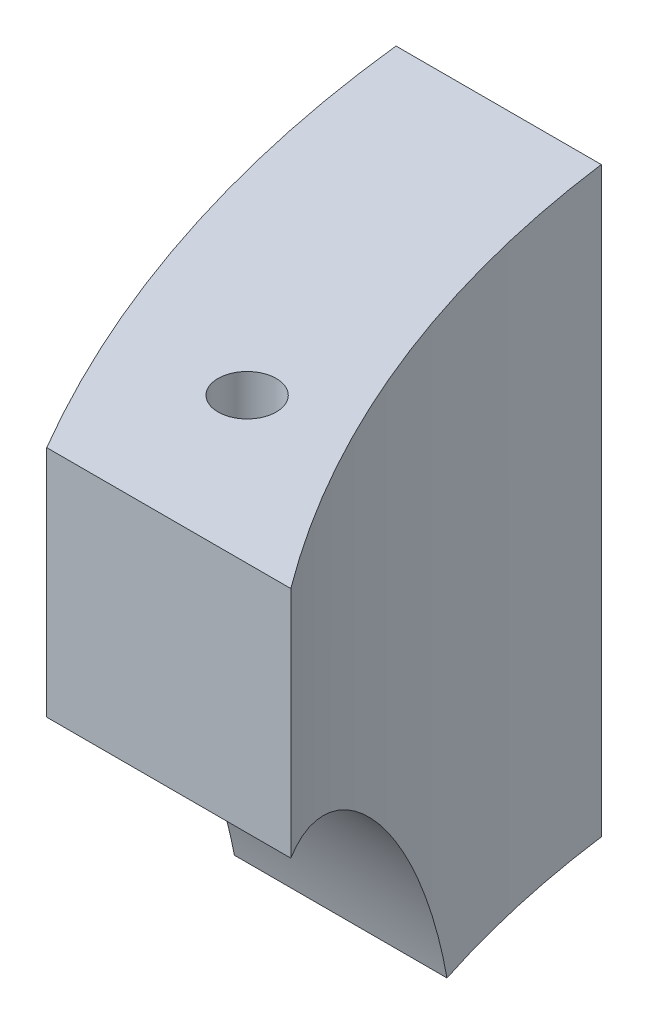
SolidWorks part; units mm, degrees
material "1023 Carbon Steel Sheet (SS)"
ref_plane "Front Plane" through (0, 0, 0) normal (0, 0, 1) x (1, 0, 0)
ref_plane "Top Plane" through (0, 0, 0) normal (0, 1, 0) x (1, 0, 0)
ref_plane "Right Plane" through (0, 0, 0) normal (1, 0, 0) x (0, 0, -1)
sketch "Sketch1" plane through (0, 0, 0) normal (0, 1, 0) x (1, 0, 0)
  line L0 (-1000, 0) -> (-104.805, 0) construction
  line L1 (0, -1000) -> (0, 49000) construction
  line L2 (91.805, -10) -> (90.2527, -10)
  line L3 (-76.805, 0) -> (76.805, 0)
  line L7 (-91.805, -10) -> (-90.2527, -10)
  line L9 (104.805, 0) -> (49000, 0) construction
  line L10 (-76.805, 0) -> (-76.805, 20)
  line L12 (-76.805, 0) -> (76.805, 0) construction
  line L13 (91.805, 20) -> (91.805, -10)
  line L14 (76.805, 20) -> (91.805, 20)
  line L17 (-76.805, 20) -> (-91.805, 20)
  line L18 (76.805, 0) -> (76.805, 20)
  line L19 (-91.805, 20) -> (-91.805, -10)
  arc A0 (-90.2527, -10) -> (90.2527, -10) centre (0, 0) ccw
  arc A1 (-76.805, 0) -> (76.805, 0) centre (0, 0) ccw
  dimension "D1" = 181.61
  dimension "D2" = 14
  dimension "D3" = 30
  dimension "D4" = 15
extrude "Boss-Extrude1" add sketch "Sketch1" against normal blind 60
sketch "Sketch25" plane through (0, -60, 0) normal (0, -1, 0) x (-1, 0, 0)
  line L0 (76.805, 20) -> (91.805, -10)
  line L1 (91.805, -10) -> (76.805, -10)
  line L2 (76.805, -10) -> (91.805, 20)
  line L3 (-91.805, -10) -> (-76.805, 20)
  line L4 (81.555, -3.5) -> (87.055, -3.5)
  line L5 (81.555, -3.5) -> (81.555, 13.5)
  line L6 (81.555, 13.5) -> (87.055, 13.5)
  line L7 (87.055, -3.5) -> (87.055, 13.5)
  line L8 (81.555, -3.5) -> (87.055, 13.5) construction
  line L9 (81.555, 13.5) -> (87.055, -3.5) construction
  line L10 (-76.805, 20) -> (-77.8097, -10)
  line L11 (-77.8097, -10) -> (-91.805, -10)
  line L12 (-77.8097, -10) -> (-91.805, 20)
  line L14 (-87.055, -3.5) -> (-81.555, -3.5)
  line L15 (-87.055, -3.5) -> (-87.055, 13.5)
  line L16 (-87.055, 13.5) -> (-81.555, 13.5)
  line L17 (-81.555, -3.5) -> (-81.555, 13.5)
  line L18 (-87.055, -3.5) -> (-81.555, 13.5) construction
  line L19 (-87.055, 13.5) -> (-81.555, -3.5) construction
  point P4 (84.305, 5)
  point P16 (-84.305, 5)
  dimension "D1" = 5.5
  dimension "D2" = 17
  dimension "D3" = 17
  dimension "D4" = 5.5
extrude "Boss-Extrude3" add sketch "Sketch25" along normal blind 20 contours L15 L16 L17 L14 | L5 L6 L7 L4
ref_plane "Plane4" through (0, 0, 90) normal (0, 0, 1) x (1, 0, 0)
fillet "Fillet1" radius 2.3 8 edges at (84.305, -60, 3.5) (81.555, -60, -5) (84.305, -60, -13.5) (87.055, -60, -5) (-87.055, -60, -5) (-84.305, -60, -13.5) (-84.305, -60, 3.5) (-81.555, -60, -5)
sketch "Sketch28" plane through (91.805, 0, 0) normal (1, 0, 0) x (0, 0, -1)
  line L2 (20, 0) -> (20, -60)
  line L3 (20, -60) -> (-10, -60)
  line L4 (-10, 0) -> (-10, -60)
  line L5 (9, -37) -> (1, -37)
  line L6 (9, -37) -> (9, -47)
  line L7 (9, -47) -> (1, -47)
  line L8 (1, -37) -> (1, -47)
  line L9 (9, -37) -> (1, -47) construction
  line L10 (9, -47) -> (1, -37) construction
  point P7 (5, -42)
  dimension "D1" = 11
  dimension "D2" = 8
  dimension "D3" = 10
  dimension "D4" = 13
extrude "Cut-Extrude17" cut sketch "Sketch28" against normal blind 265 contours L5 L8 L7 L6
sketch "Sketch30" plane through (0, 0, -20) normal (0, 0, -1) x (-1, 0, 0)
  line L0 (-91.805, -60) -> (-91.805, 0) construction
  line L1 (91.805, 0) -> (-91.805, 0)
  line L2 (91.805, 0) -> (91.805, -30)
  line L3 (91.805, -30) -> (-91.805, -30)
  line L4 (-91.805, 0) -> (-91.805, -30)
  dimension "D1" = 30
extrude "Cut-Extrude19" cut sketch "Sketch30" against normal through all both and the other way through all
sketch "Sketch32" plane through (0, 0, -20) normal (0, 0, -1) x (-1, 0, 0)
  line L0 (-91.805, -60) -> (-91.805, -30) construction
  line L1 (-82.805, -39) -> (-85.805, -39)
  line L2 (-82.805, -39) -> (-82.805, -53)
  line L3 (-82.805, -53) -> (-85.805, -53)
  line L4 (-85.805, -39) -> (-85.805, -53)
  line L8 (-76.805, -30) -> (-91.805, -30) construction
  line L9 (0, 0) -> (0, -102.7115)
  line L10 (53.2739, -37) -> (53.2739, -51)
  line L11 (-66.6352, -37) -> (-63.6352, -37)
  line L12 (-66.6352, -37) -> (-66.6352, -51)
  line L13 (-66.6352, -51) -> (-63.6352, -51)
  line L14 (-63.6352, -37) -> (-63.6352, -51)
  line L15 (-50.2739, -37) -> (-53.2739, -37)
  line L16 (-50.2739, -37) -> (-50.2739, -51)
  line L17 (-50.2739, -51) -> (-53.2739, -51)
  line L18 (-53.2739, -37) -> (-53.2739, -51)
  line L19 (50.2739, -51) -> (53.2739, -51)
  line L20 (50.2739, -37) -> (50.2739, -51)
  line L21 (50.2739, -37) -> (53.2739, -37)
  line L22 (63.6352, -37) -> (63.6352, -51)
  line L23 (66.6352, -51) -> (63.6352, -51)
  line L24 (66.6352, -37) -> (66.6352, -51)
  line L25 (66.6352, -37) -> (63.6352, -37)
  line L26 (85.805, -39) -> (85.805, -53)
  line L27 (82.805, -53) -> (85.805, -53)
  line L28 (82.805, -39) -> (82.805, -53)
  line L29 (82.805, -39) -> (85.805, -39)
  point P19 (-51.7739, -37)
  point P20 (-65.1352, -37)
  dimension "D1" = 3
  dimension "D2" = 6
  dimension "D3" = 14
  dimension "D4" = 9
  dimension "D5" = 1.5
  dimension "D6" = 1.5
extrude "Cut-Extrude20" cut sketch "Sketch32" against normal through all both and the other way through all contours L14 L11 L12 L13 | L15 L18 L17 L16 | L4 L3 L2 L1 | L24 L23 L22 L25 | L10 L19 L20 L21 | L28 L27 L26 L29
sketch "Sketch33" plane through (0, -60, 0) normal (0, -1, 0) x (-1, 0, 0)
  line L0 (90.2527, -10) -> (76.1512, -10)
  line L2 (73.8985, -52.7689) -> (61.5906, -45.8869)
  arc A0 (-76.805, 0) -> (76.805, 0) centre (0, 0) ccw construction
  arc A1 (76.1512, -10) -> (61.5906, -45.8869) centre (0, 0) cw
  arc A2 (90.2527, -10) -> (73.8985, -52.7689) centre (0, 0) cw
  arc A3 (-90.2527, -10) -> (90.2527, -10) centre (0, 0) ccw construction
extrude "Boss-Extrude4" add sketch "Sketch33" along normal blind 40
sketch "Sketch37" plane through (0, 0, 0) normal (1, 0, 0) x (0, 0, -1)
  line L0 (-0.8813, -100) -> (-23.6906, -100)
  line L1 (-45.8869, -59.9172) -> (-45.8869, -76.0376)
  line L2 (-45.8869, -59.9172) -> (-66.9482, -59.9172)
  line L3 (-66.9482, -59.9172) -> (-63.7464, -92.4419)
  line L4 (-63.7464, -92.4419) -> (-47.5718, -115.3465)
  line L5 (-47.5718, -115.3465) -> (-8.0864, -115.3465)
  line L6 (-8.0864, -115.3465) -> (-0.8813, -100)
  line L7 (-45.8869, -100) -> (-10, -100) construction
  line L8 (-45.8869, -100) -> (-45.8869, -60) construction
  arc A0 (-23.6906, -100) -> (-45.8869, -76.0376) centre (-56.36, -108.0002) ccw
extrude "Cut-Extrude21" cut sketch "Sketch37" against normal blind 90 contours L6 L0 A0 L1 L2 L3 L4 L5
sketch "Sketch38" plane through (0, 0, 0) normal (1, 0, 0) x (0, 0, -1)
  line L0 (-90.805, -60) -> (-10, -60) construction
  line L1 (20, -30) -> (-90.805, -30)
  line L2 (20, -30) -> (20, -60)
  line L3 (-10, -60) -> (-90.805, -60)
  line L4 (-90.805, -30) -> (-90.805, -60)
  line L5 (-90.805, -30) -> (-90.805, -60) construction
  line L6 (-10, -100) -> (-10, -60) construction
  line L8 (20, -60) -> (20, -100)
  line L9 (20, -100) -> (-10, -100)
  line L10 (-10, -60) -> (-10, -100)
extrude "Cut-Extrude22" cut sketch "Sketch38" against normal through all both and the other way through all
sketch "Sketch39" plane through (0, 0, 10) normal (0, 0, -1) x (-1, 0, 0)
  circle A0 centre (82.2527, -87.5) radius 2
  dimension "D3" = 4
  dimension "D1" = 12.5
  dimension "D2" = 8
sketch "Sketch40" plane through (0, -60, 0) normal (0, 1, 0) x (1, 0, 0)
  circle A0 centre (-74.5906, -35.8869) radius 2
  dimension "D3" = 4
  dimension "D1" = 10
  dimension "D2" = 13
extrude "Cut-Extrude23" cut sketch "Sketch39" against normal blind 88
extrude "Cut-Extrude24" cut sketch "Sketch40" against normal blind 88
